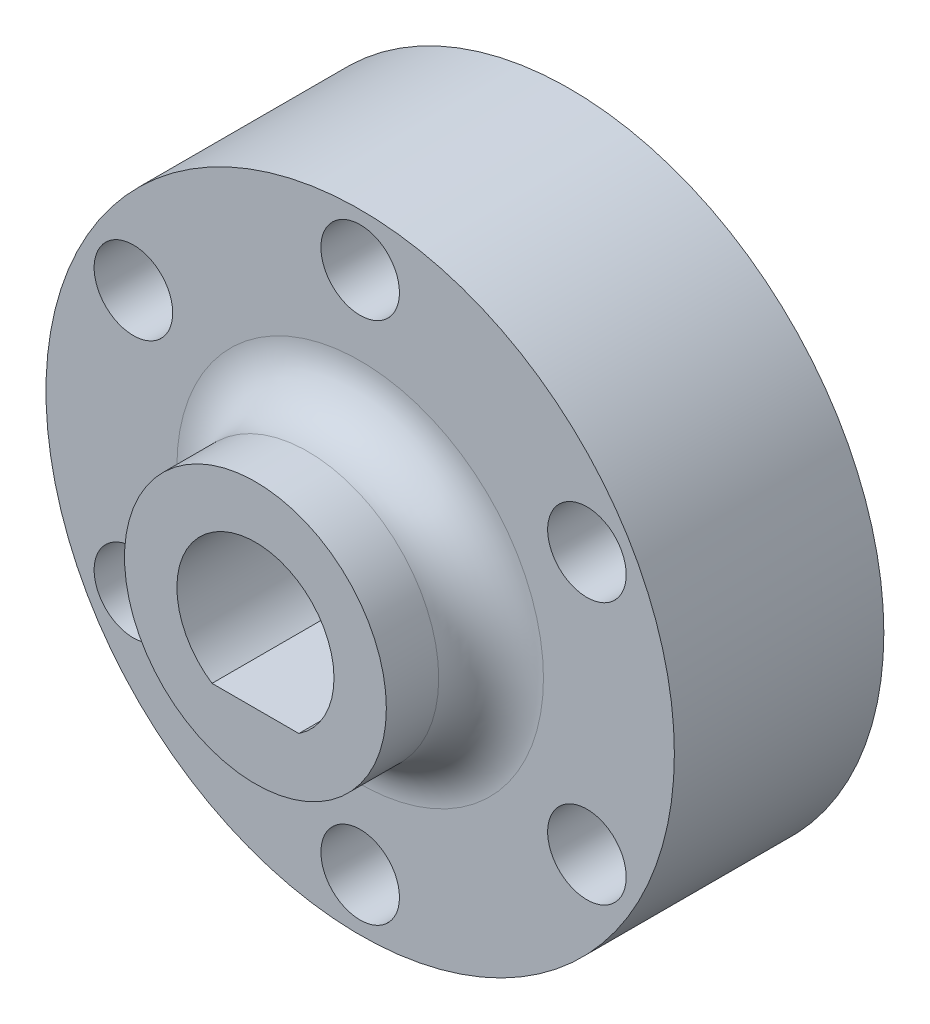
SolidWorks part; units mm, degrees
ref_plane "Plan de face" through (0, 0, 0) normal (0, 0, 1) x (1, 0, 0)
ref_plane "Plan de dessus" through (0, 0, 0) normal (0, 1, 0) x (1, 0, 0)
ref_plane "Plan de droite" through (0, 0, 0) normal (1, 0, 0) x (0, 0, -1)
sketch "Sketch1" plane through (0, 0, 0) normal (0, 0, 1) x (1, 0, 0)
  circle A0 centre (0, 0) radius 12
  circle A1 centre (0, 0) radius 10
  circle A2 centre (0, 10) radius 1.5
  circle A3 centre (0, 0) radius 3
  circle A4 centre (8.6603, 5) radius 1.5
  circle A5 centre (8.6603, -5) radius 1.5
  circle A6 centre (0, -10) radius 1.5
  circle A7 centre (-8.6603, -5) radius 1.5
  circle A8 centre (-8.6603, 5) radius 1.5
  point P19 (0, 0)
  dimension "D1" = 3
  dimension "D2" = 20
  dimension "D3" = 24
  dimension "D5" = 6
  dimension "D4" = 6
extrude "Boss-Extrude1" add sketch "Sketch1" along normal blind 8 contours A0 A8 A1 A2 A4 A5 A6 A7 | A8 A1 A7 A6 A5 A4 A2 A3
sketch "Sketch2" plane through (0, 0, 8) normal (0, 0, 1) x (1, 0, 0)
  line L0 (-1.6583, -2.5) -> (1.6583, -2.5)
  circle A0 centre (0, 0) radius 5
  circle A1 centre (0, 0) radius 3
  circle A2 centre (0, 0) radius 3 construction
  circle M11 centre (0, 0) radius 3
  dimension "D2" = 10
  dimension "D1" = 2.5
extrude "Boss-Extrude2" add sketch "Sketch2" along normal blind 4 and the other way up to surface contours A0 M11 | L0 M11
fillet "Fillet1" radius 2 1 edges at (5, 0, 8)
